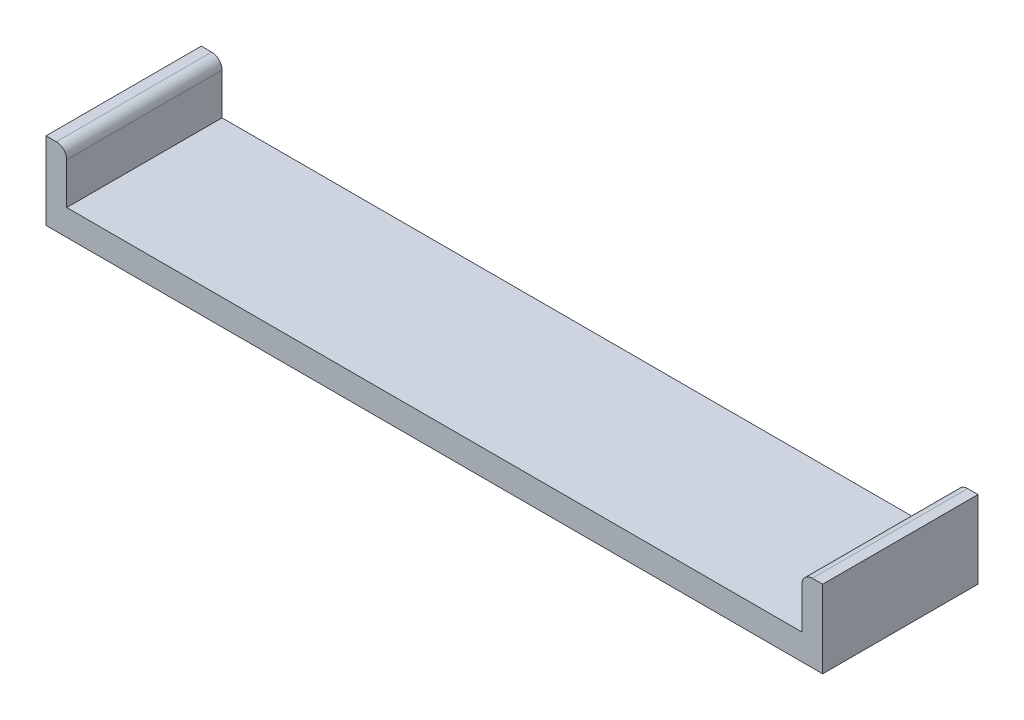
SolidWorks part; units mm, degrees
ref_plane "Front Plane" through (0, 0, 0) normal (0, 0, 1) x (1, 0, 0)
ref_plane "Top Plane" through (0, 0, 0) normal (0, 1, 0) x (1, 0, 0)
ref_plane "Right Plane" through (0, 0, 0) normal (1, 0, 0) x (0, 0, -1)
sketch "Sketch1" plane through (0, 0, 0) normal (0, 1, 0) x (1, 0, 0)
  line L1 (0, 0) -> (150, 0)
  line L2 (0, 0) -> (0, 30)
  line L3 (0, 30) -> (150, 30)
  line L4 (150, 0) -> (150, 30)
  dimension "D1" = 150
  dimension "D2" = 30
extrude "Boss-Extrude1" add sketch "Sketch1" along normal blind 5
sketch "Sketch3" plane through (0, 5, 0) normal (0, 1, 0) x (1, 0, 0)
  line L0 (0, 0) -> (150, 0) construction
  line L1 (150, 30) -> (146, 30)
  line L2 (150, 30) -> (150, 0)
  line L3 (150, 0) -> (146, 0)
  line L4 (146, 30) -> (146, 0)
  dimension "D1" = 4
extrude "Boss-Extrude2" add sketch "Sketch3" along normal blind 10
sketch "Sketch4" plane through (0, 5, 0) normal (0, 1, 0) x (1, 0, 0)
  line L0 (0, 0) -> (146, 0) construction
  line L1 (0, 30) -> (4, 30)
  line L2 (0, 30) -> (0, 0)
  line L3 (0, 0) -> (4, 0)
  line L4 (4, 30) -> (4, 0)
  dimension "D1" = 4
extrude "Boss-Extrude3" add sketch "Sketch4" along normal blind 10
fillet "Fillet1" radius 2 2 edges at (146, 15, -15) (4, 15, -15)
